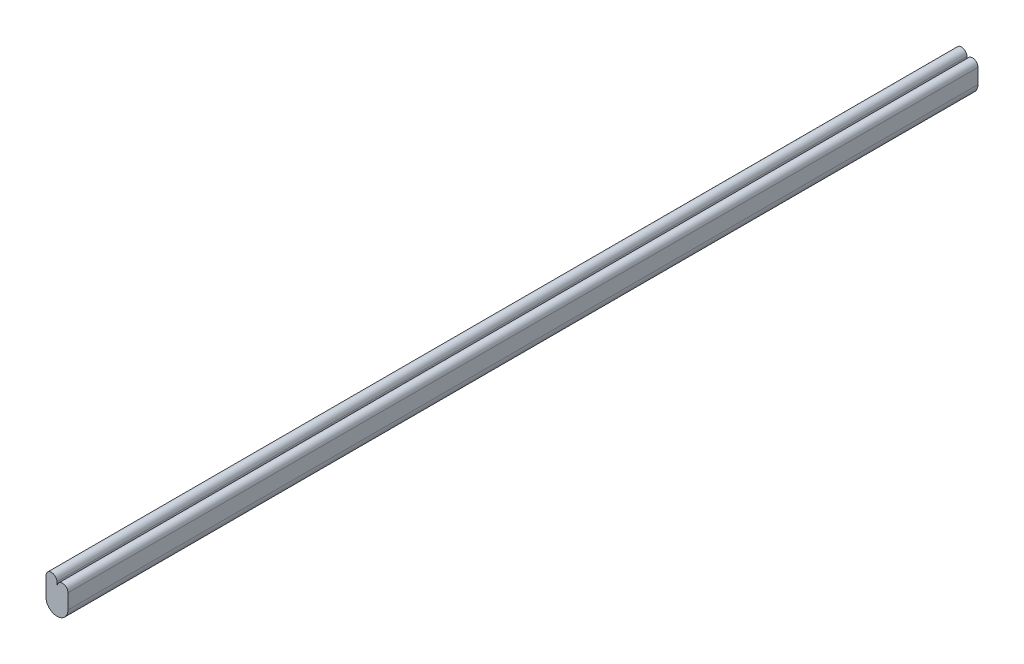
SolidWorks part; units mm, degrees
material "PVC 0.007 Plasticized"
ref_plane "Front Plane" through (0, 0, 0) normal (0, 0, 1) x (1, 0, 0)
ref_plane "Top Plane" through (0, 0, 0) normal (0, 1, 0) x (1, 0, 0)
ref_plane "Right Plane" through (0, 0, 0) normal (1, 0, 0) x (0, 0, -1)
sketch "Sketch1" plane through (0, 0, 0) normal (0, 0, 1) x (1, 0, 0)
  line L6 (-0.05, 12.025) -> (-0.05, 0)
  line L9 (0.05, 0) -> (0.05, 9.525)
  line L11 (-7, 12.025) -> (-7, 0)
  line L12 (7, 0) -> (7, 9.525)
  line L14 (0, 13) -> (0, 0) construction
  arc A12 (-7, 0) -> (7, 0) centre (0, 0) ccw
  arc A13 (-0.05, 12.025) -> (-7, 12.025) centre (-3.525, 12.025) ccw
  arc A14 (0.05, 9.525) -> (7, 9.525) centre (3.525, 9.525) cw
  arc A15 (-0.05, 0) -> (0.05, 0) centre (0, 0) ccw construction
  arc A16 (0.05, 0) -> (-0.05, 0) centre (0, 0) cw
  point P4 (-3.525, 15.5)
  point P11 (3.525, 13)
  point P14 (0, -7)
  dimension "D2" = 20
  dimension "D3" = 14
  dimension "D1" = 0.1
  dimension "D4" = 22.5
extrude "Boss-Extrude4" add sketch "Sketch1" along normal blind 580 contours L11 A12 L12 A14 L9 A16 L6 A13
